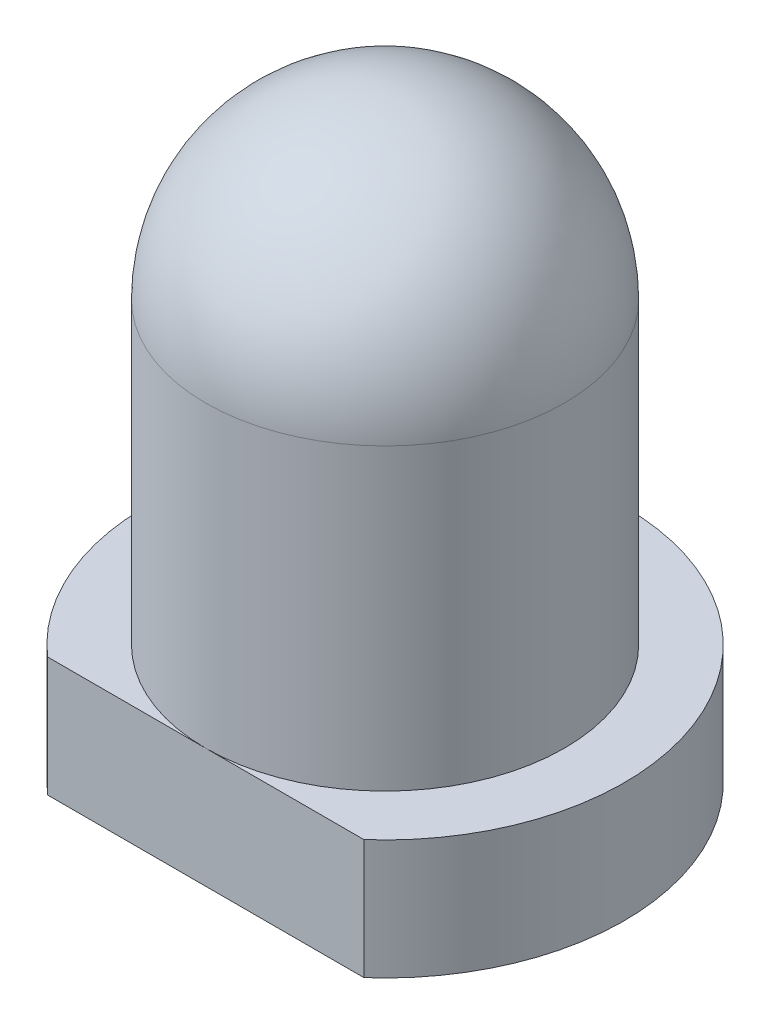
SolidWorks part; units mm, degrees
material "ABS PC"
ref_plane "Front Plane" through (0, 0, 0) normal (0, 0, 1) x (1, 0, 0)
ref_plane "Top Plane" through (0, 0, 0) normal (0, 1, 0) x (1, 0, 0)
ref_plane "Right Plane" through (0, 0, 0) normal (1, 0, 0) x (0, 0, -1)
sketch "Sketch1" plane through (0, 0, 0) normal (0, 1, 0) x (1, 0, 0)
  circle A0 centre (0, 0) radius 1.5
  dimension "D1" = 3
extrude "Base" add sketch "Sketch1" along normal blind 5
fillet "Dome" radius 1.5 1 edges at (0, 5, 1.5)
sketch "BaseCutSketch" plane through (0, 0, 0) normal (0, 1, 0) x (1, 0, 0)
  line L0 (1.3229, -1.5) -> (-1.3229, -1.5)
  arc A0 (1.3229, -1.5) -> (-1.3229, -1.5) centre (0, 0) ccw
  circle A2 centre (0, 0) radius 1.5 construction
  dimension "D1" = 4
extrude "BaseCut" add sketch "BaseCutSketch" along normal blind 1
